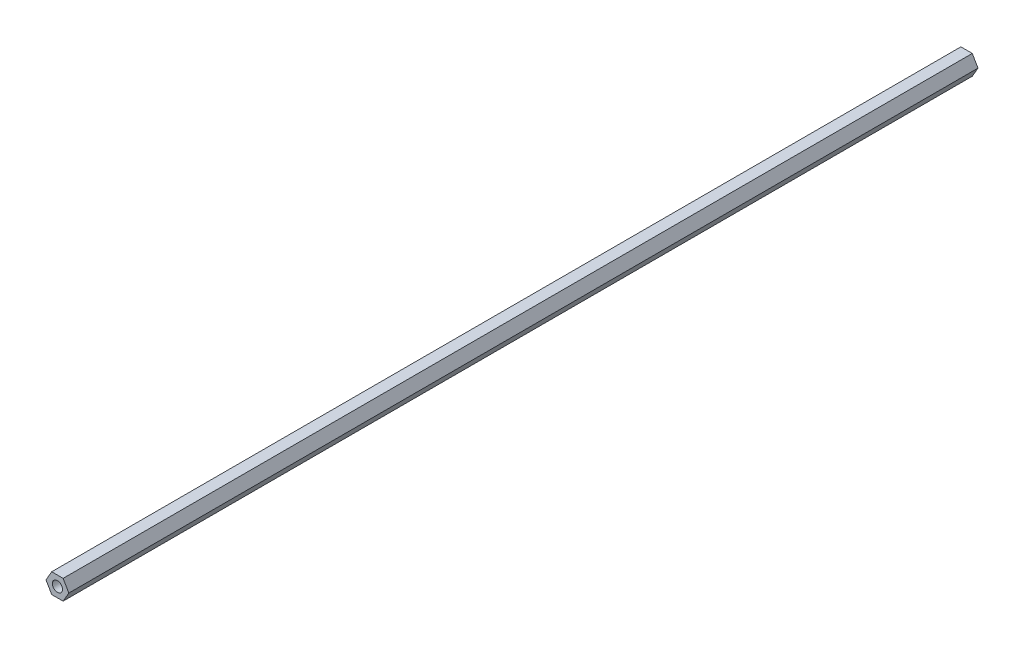
SolidWorks part; units mm, degrees
material "6061 Alloy"
ref_plane "Front Plane" through (0, 0, 0) normal (0, 0, 1) x (1, 0, 0)
ref_plane "Top Plane" through (0, 0, 0) normal (0, 1, 0) x (1, 0, 0)
ref_plane "Right Plane" through (0, 0, 0) normal (1, 0, 0) x (0, 0, -1)
sketch "Sketch1" plane through (0, 0, 0) normal (0, 0, 1) x (1, 0, 0)
  line L1 (-3.6662, 6.35) -> (-7.3323, 0)
  line L2 (-7.3323, 0) -> (-3.6662, -6.35)
  line L3 (-3.6662, -6.35) -> (3.6662, -6.35)
  line L4 (3.6662, -6.35) -> (7.3323, 0)
  line L5 (7.3323, 0) -> (3.6662, 6.35)
  line L6 (3.6662, 6.35) -> (-3.6662, 6.35)
  circle A0 centre (0, 0) radius 6.35 construction
  circle A1 centre (0, 0) radius 3.2639
  dimension "D1" = 12.7
  dimension "D2" = 6.5278
extrude "Boss-Extrude1" add sketch "Sketch1" along normal blind 584.2
